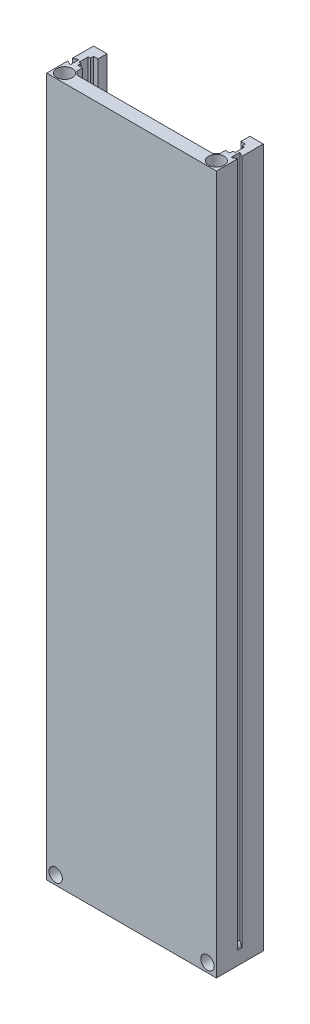
SolidWorks part; units mm, degrees
ref_plane "Přední rovina" through (0, 0, 0) normal (0, 0, 1) x (1, 0, 0)
ref_plane "Horní rovina" through (0, 0, 0) normal (0, 1, 0) x (1, 0, 0)
ref_plane "Pravá rovina" through (0, 0, 0) normal (1, 0, 0) x (0, 0, -1)
sketch "Skica1" plane through (0, 0, 0) normal (0, 0, 1) x (1, 0, 0)
  line L0 (-34, 146) -> (0, 146) construction
  line L1 (0, 0) -> (-34, 0)
  line L2 (0, 0) -> (0, 146)
  line L3 (0, 146) -> (-34, 146)
  line L4 (-34, 0) -> (-34, 146)
  line L5 (-34, 0) -> (-34, 146) construction
  line L6 (2, -2) -> (2, 148)
  line L8 (-36, -2) -> (-36, 148)
  line L9 (2, -2) -> (0, -2)
  line L10 (0, 151.5) -> (0, 146)
  line L11 (-34, 151.5) -> (-34, 146)
  line L12 (0, 0) -> (0, -2)
  line L13 (-34, 0) -> (-34, -2)
  line L14 (-34, -2) -> (-36, -2)
  line L15 (2, -2) -> (-36, -2) construction
  line L16 (-17, 146) -> (-17.1, 151.5) construction
  line L17 (2, 148) -> (-36, 148) construction
  line L19 (-36, 151.5) -> (-17.1, 151.5) construction
  line L20 (0, 151.5) -> (2, 151.5)
  line L21 (2, 151.5) -> (2, 148)
  line L24 (-34, 151.5) -> (-36, 151.5)
  line L25 (-36, 151.5) -> (-36, 148)
  dimension "D1" = 2
extrude "Přidat vysunutím2" add sketch "Skica1" along normal blind 3 and the other way blind 4.5
sketch "Skica3" plane through (0, 0, 0) normal (-1, 0, 0) x (0, 0, 1)
  line L1 (-4.5, -2) -> (-2.5, -2)
  line L2 (-4.5, -2) -> (-4.5, 151.5)
  line L3 (-4.5, 151.5) -> (-2.5, 151.5)
  line L4 (-2.5, -2) -> (-2.5, 151.5)
  line L5 (-4.5, -2) -> (3, -2) construction
  line L6 (3, 151.5) -> (1, 151.5)
  line L7 (3, 151.5) -> (3, -2)
  line L8 (3, -2) -> (1, -2)
  line L9 (1, 151.5) -> (1, -2)
  line L10 (-1.5, 146) -> (-1.5, 0) construction
  line L11 (0, 146) -> (0, 0) construction
  line L15 (-4.5, 151.5) -> (3, 151.5) construction
  dimension "D1" = 1
  dimension "D2" = 2
  dimension "D3" = 1
  dimension "D4" = 2
  dimension "D5" = 3.5
extrude "Přidat vysunutím3" add sketch "Skica3" along normal blind 1
sketch "Skica4" plane through (0, -2, 0) normal (0, -1, 0) x (1, 0, 0)
  line L0 (0, -2.5) -> (0, 1) construction
  line L1 (0, 0) -> (0.5, 0)
  line L2 (0, 0) -> (0, -1.5)
  line L3 (0, -1.5) -> (0.5, -1.5)
  line L4 (0.5, 0) -> (0.5, -1.5)
  line L6 (0.5, -1.5) -> (0.5, -1.8)
  line L7 (0.5, -1.8) -> (0, -1.8)
  line L8 (0, -1.5) -> (0, -1.8)
  line L11 (0.5, 0) -> (0.5, 0.3)
  line L12 (0.5, 0.3) -> (0, 0.3)
  line L13 (0, 0) -> (0, 0.3)
  line M17 (0, 1) -> (0, -2.5)
  dimension "D1" = 0.5
  dimension "D2" = 0.3
  dimension "D3" = 2.1
sketch "Skica5" plane through (0, -2, 0) normal (0, -1, 0) x (1, 0, 0)
  line L0 (0, -1.5) -> (-34, -1.5) construction
  line L1 (-34, 0) -> (-34.5, 0)
  line L2 (-34, 0) -> (-34, -1.5)
  line L3 (-34, -1.5) -> (-34.5, -1.5)
  line L4 (-34.5, 0) -> (-34.5, -1.5)
  line L5 (0, 0) -> (-34, 0) construction
  line L7 (-34, -1.5) -> (-34.5, -1.5)
  line L8 (-34, -1.5) -> (-34, -1.8)
  line L9 (-34, -1.8) -> (-34.5, -1.8)
  line L10 (-34.5, -1.5) -> (-34.5, -1.8)
  line L11 (-34, 0) -> (-34.5, 0)
  line L12 (-34, 0) -> (-34, 0.3)
  line L13 (-34, 0.3) -> (-34.5, 0.3)
  line L14 (-34.5, 0) -> (-34.5, 0.3)
  line M13 (-34, -4.5) -> (-34, 3)
  dimension "D1" = 0.5
  dimension "D2" = 0.3
extrude "Odebrat vysunutím2" cut sketch "Skica5" against normal through all contours L3 L10 L9 M13 | L1 L4 L3 M13 | L14 L1 L13 M13
sketch "Skica6" plane through (0, -2, 0) normal (0, -1, 0) x (1, 0, 0)
  line L1 (-34, 3) -> (-33, 3)
  line L2 (-34, 3) -> (-34, 1)
  line L3 (-34, 1) -> (-33, 1)
  line L4 (-33, 3) -> (-33, 1)
  line L5 (-34, -4.5) -> (-33, -4.5)
  line L6 (-34, -4.5) -> (-34, -2.5)
  line L7 (-34, -2.5) -> (-33, -2.5)
  line L8 (-33, -4.5) -> (-33, -2.5)
  line L12 (-34, 0.3) -> (-34.5, 0.3) construction
  line L13 (-34, -1.8) -> (-34.5, -1.8) construction
  dimension "D1" = 1
  dimension "D2" = 0.7
  dimension "D3" = 0.7
extrude "Přidat vysunutím4" add sketch "Skica6" against normal through all
sketch "Skica7" plane through (0, 0, 3) normal (0, 0, 1) x (1, 0, 0)
  line L0 (-33, 151.5) -> (-36, 151.5) construction
  line L1 (-36, 151.5) -> (2, 151.5)
  line L2 (-36, 151.5) -> (-36, -2)
  line L3 (-36, -2) -> (2, -2)
  line L4 (2, 151.5) -> (2, -2)
extrude "Přidat vysunutím5" add sketch "Skica7" along normal blind 3
sketch "Skica8" plane through (0, -2, 0) normal (0, -1, 0) x (1, 0, 0)
  line L0 (-33, -4.5) -> (-36, -4.5) construction
  line L1 (2, 6) -> (-36, 6)
  line L2 (2, 6) -> (2, -4.5)
  line L3 (2, -4.5) -> (-36, -4.5)
  line L4 (-36, 6) -> (-36, -4.5)
extrude "Přidat vysunutím6" add sketch "Skica8" along normal blind 3
extrude "Odebrat vysunutím3" cut sketch "Skica4" against normal through all contours L11 L12 L1 M17 | L4 L1 L3 M17 | L7 L6 L3 M17
ref_plane "Rovina2" through (-33, -2, 3) normal (0, -1, 0) x (-1, 0, 0)
sketch "Skica11" plane through (-33, -2, 3) normal (0, -1, 0) x (1, 0, 0)
  line L0 (-3, 3) -> (-3, -7.5) construction
  line L3 (-1.9533, -3.25) -> (-2, -3.25)
  line L4 (-2, -1.25) -> (-2, -3.25)
  line L5 (-3, -2.25) -> (-2, -3.25) construction
  line L6 (-3, -2.25) -> (-2, -1.25) construction
  line L7 (35, -7.5) -> (35, 3) construction
  line L12 (16, 3) -> (16, -7.5) construction
  line L13 (35, 3) -> (-3, 3) construction
  line L14 (-3, -7.5) -> (35, -7.5) construction
  line L15 (-3, -2.75) -> (-3, -1.75)
  line L16 (-3, -1.75) -> (-3, -2.25) construction
  line L17 (-3, -2.25) -> (-3, -2.75) construction
  line L18 (-2, -1.25) -> (-2, -2.25) construction
  line L19 (-1.9533, -1.25) -> (-1.9533, -2.25) construction
  line L20 (-1.9533, -1.75) -> (-3, -1.75) construction
  line L21 (-1.9533, -2.25) -> (-1.9533, -3.25) construction
  line L22 (-1.9533, -2.75) -> (-3, -2.75) construction
  line L23 (-2, -3.25) -> (-3, -2.75)
  line L24 (-2, -1.25) -> (-3, -1.75)
  line L25 (-1.9533, -1.25) -> (-2, -1.25)
  line L26 (33.9533, -2.75) -> (35, -2.75) construction
  line L27 (33.9533, -2.25) -> (33.9533, -3.25) construction
  line L28 (33.9533, -1.75) -> (35, -1.75) construction
  line L29 (33.9533, -1.25) -> (33.9533, -2.25) construction
  line L30 (34, -1.25) -> (34, -2.25) construction
  line L31 (35, -2.25) -> (35, -2.75) construction
  line L32 (35, -1.75) -> (35, -2.25) construction
  line L33 (35, -2.25) -> (34, -1.25) construction
  line L34 (35, -2.25) -> (34, -3.25) construction
  line L35 (33.9533, -1.25) -> (34, -1.25)
  line L36 (34, -1.25) -> (35, -1.75)
  line L37 (34, -3.25) -> (35, -2.75)
  line L38 (35, -2.75) -> (35, -1.75)
  line L39 (34, -1.25) -> (34, -3.25)
  line L40 (33.9533, -3.25) -> (34, -3.25)
  point P0 (-3, -2.25)
  point P7 (35, -2.25)
  dimension "D1" = 1
  dimension "D2" = 2
  dimension "D3" = 1
extrude "Odebrat vysunutím6" cut sketch "Skica11" along a picked direction on the side against the normal blind 153.5 contours L4 L24 L15 L23 | L36 L39 L37 L38
sketch "Skica14" plane through (0, 0, -4.5) normal (0, 0, -1) x (-1, 0, 0)
  line L0 (36, 151.5) -> (36, -5) construction
  line L1 (36, -5) -> (-2, -5) construction
  line L2 (17, -5) -> (17, -2) construction
  line L3 (33, -2) -> (1, -2) construction
  circle A0 centre (34, -3) radius 1.5
  circle A1 centre (0, -3) radius 1.5
  dimension "D1" = 3
  dimension "D2" = 2
  dimension "D3" = 2
extrude "Odebrat vysunutím9" cut sketch "Skica14" against normal up to vertex
sketch "Skica22" plane through (0, 0, 6) normal (0, 0, 1) x (1, 0, 0)
  circle A0 centre (-34, -3) radius 1.5
  circle A1 centre (-34, -3) radius 2
  circle A2 centre (0, -3) radius 1.5
  circle A3 centre (0, -3) radius 2
  point P8 (0, -3)
  point P9 (0, -3)
extrude "Přidat vysunutím12" add sketch "Skica22" against normal up to vertex (10.5 mm away)
sketch "Skica15" plane through (0, 0, -4.5) normal (0, 0, -1) x (-1, 0, 0)
  circle A0 centre (0, -3) radius 1.75
  circle A2 centre (34, -3) radius 1.75
  circle A4 centre (34, -3) radius 2
  circle A5 centre (0, -3) radius 2
extrude "Přidat vysunutím7" add sketch "Skica15" against normal up to surface (7.5 mm away) up to face at (-17, 49.4267, 3)
sketch "Skica16" plane through (0, 151.5, 0) normal (0, 1, 0) x (1, 0, 0)
  line L0 (2, -1.25) -> (2, -6) construction
  line L2 (2, -6) -> (-36, -6) construction
  line L3 (-17, -6) -> (-17, -3) construction
  line L4 (-1, -3) -> (-33, -3) construction
  circle A0 centre (0, -4) radius 1.75
  circle A1 centre (-34, -4) radius 1.75
  dimension "D1" = 3.5
  dimension "D2" = 2
  dimension "D3" = 2
sketch "Skica17" plane through (0, 151.5, 0) normal (0, 1, 0) x (1, 0, 0)
  line L0 (2, -1.25) -> (2, -6) construction
  circle A0 centre (0, -4) radius 2
  circle A1 centre (0, -4) radius 1.75
  circle A2 centre (0, -4) radius 1.75 construction
  circle A3 centre (-34, -4) radius 2
  circle A4 centre (-34, -4) radius 1.75
  circle A5 centre (-34, -4) radius 1.75 construction
extrude "Odebrat vysunutím10" cut sketch "Skica16" against normal blind 4
extrude "Přidat vysunutím10" add sketch "Skica17" against normal blind 4
sketch "Skica18" plane through (0, 147.5, 0) normal (0, -1, 0) x (1, 0, 0)
  line L0 (-1, 2.2679) -> (-1, 2.5639) construction
  line L1 (-33, 2.2679) -> (-33, 3)
  line L2 (-33, 3) -> (-32.2679, 3)
  line L3 (-1.7321, 3) -> (-1, 3)
  line L4 (-1, 3) -> (-1, 2.2679)
  arc A0 (-1.7321, 3) -> (-1, 2.2679) centre (-1, 3) ccw
  arc A1 (-33, 2.2679) -> (-32.2679, 3) centre (-33, 3) ccw
  arc A2 (-33, 2.2679) -> (-32.2679, 3) centre (-34, 4) ccw construction
extrude "Přidat vysunutím11" add sketch "Skica18" along normal blind 2
